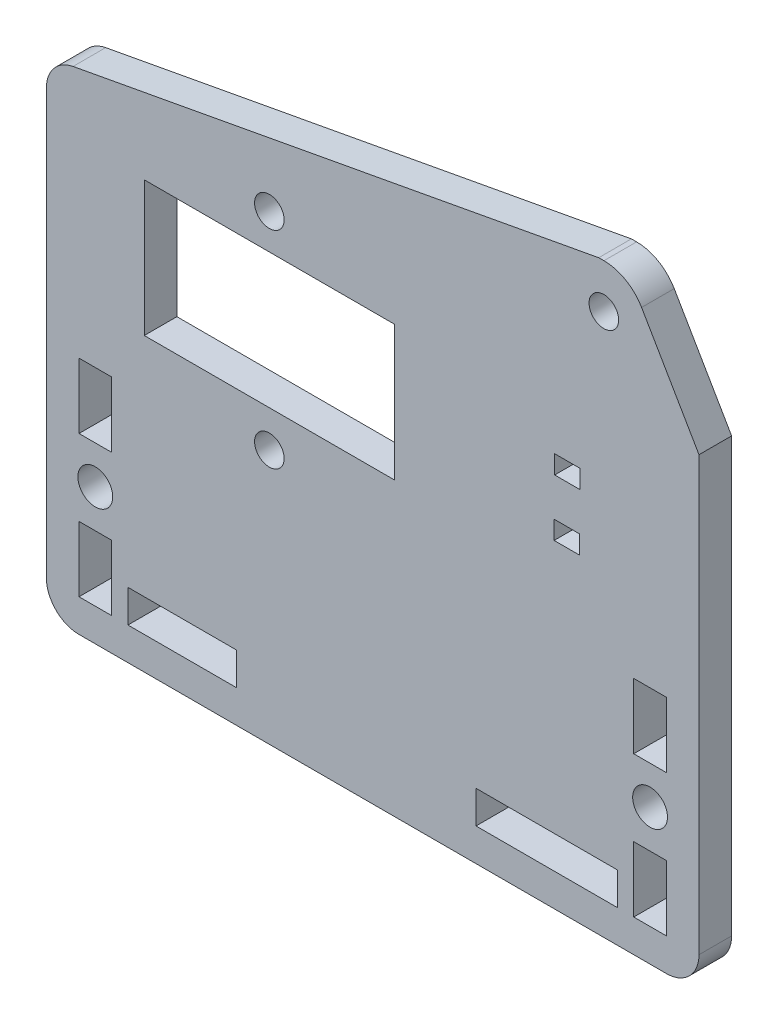
SolidWorks part; units mm, degrees
ref_plane "前视基准面" through (0, 0, 0) normal (0, 0, 1) x (1, 0, 0)
ref_plane "上视基准面" through (0, 0, 0) normal (0, 1, 0) x (1, 0, 0)
ref_plane "右视基准面" through (0, 0, 0) normal (1, 0, 0) x (0, 0, -1)
ref_plane "基准面4" through (0, 0, 0) normal (0, 0, -1) x (-1, 0, 0)
sketch "草图1" plane through (0, 0, 0) normal (0, 0, -1) x (-1, 0, 0)
  line L0 (-3.001, -11.9653) -> (-6.001, -11.9653)
  line L1 (-6.001, -11.9653) -> (-6.001, -5.9643)
  line L2 (-6.001, -5.9643) -> (-3.001, -5.9643)
  line L3 (-3.001, -5.9643) -> (-3.001, -11.9653)
  line L4 (-57, -27.9644) -> (-3, -27.9644)
  line L5 (0, -24.9644) -> (0, 14.0356)
  line L6 (-2.4546, 16.9856) -> (-50.7826, 25.9213)
  line L7 (-50.7826, 25.9213) -> (-51.2628, 25.9213)
  line L8 (-54.7215, 23.9306) -> (-60, 14.8445)
  line L9 (-60, 14.8445) -> (-60, -24.9644)
  line L10 (-3.001, -18.9633) -> (-3.001, -24.9643)
  line L11 (-3.001, -24.9643) -> (-6.001, -24.9643)
  line L12 (-6.001, -24.9643) -> (-6.001, -18.9633)
  line L13 (-6.001, -18.9633) -> (-3.001, -18.9633)
  line L14 (-54, -18.9633) -> (-54, -24.9643)
  line L15 (-54, -24.9643) -> (-57, -24.9643)
  line L16 (-57, -24.9643) -> (-57, -18.9633)
  line L17 (-57, -18.9633) -> (-54, -18.9633)
  line L18 (-54, -5.9643) -> (-54, -11.9653)
  line L19 (-54, -11.9653) -> (-57, -11.9653)
  line L20 (-57, -11.9653) -> (-57, -5.9643)
  line L21 (-57, -5.9643) -> (-54, -5.9643)
  line L22 (-7.5, -21.9643) -> (-7.5, -24.9643)
  line L23 (-7.5, -24.9643) -> (-17.5, -24.9643)
  line L24 (-17.5, -24.9643) -> (-17.5, -21.9643)
  line L25 (-17.5, -21.9643) -> (-7.5, -21.9643)
  line L26 (-39.5, -21.9643) -> (-39.5, -24.9643)
  line L27 (-39.5, -24.9643) -> (-52.499, -24.9643)
  line L28 (-52.499, -24.9643) -> (-52.499, -21.9643)
  line L29 (-52.499, -21.9643) -> (-39.5, -21.9643)
  line L30 (-46.731, 8.2907) -> (-46.731, 6.5977)
  line L31 (-46.731, 6.5977) -> (-49.06, 6.5977)
  line L32 (-49.06, 6.5977) -> (-49.06, 8.2907)
  line L33 (-49.06, 8.2907) -> (-46.731, 8.2907)
  line L34 (-46.679, 3.0517) -> (-46.679, 1.3587)
  line L35 (-46.679, 1.3587) -> (-49.008, 1.3587)
  line L36 (-49.008, 1.3587) -> (-49.008, 3.0517)
  line L37 (-49.008, 3.0517) -> (-46.679, 3.0517)
  line L38 (-9, 11.2347) -> (-9, -1.1643)
  line L39 (-9, -1.1643) -> (-32, -1.1643)
  line L40 (-32, -1.1643) -> (-32, 11.2347)
  line L41 (-32, 11.2347) -> (-9, 11.2347)
  arc A0 (-60, -24.9644) -> (-57, -27.9644) centre (-57, -24.9644) ccw
  arc A1 (-3, -27.9644) -> (0, -24.9644) centre (-3, -24.9644) ccw
  arc A2 (0, 14.0356) -> (-2.4546, 16.9856) centre (-3, 14.0356) ccw
  arc A3 (-51.2628, 25.9213) -> (-54.7215, 23.9306) centre (-51.2628, 21.9213) ccw
  circle A4 centre (-55.5, -15.4643) radius 1.359
  circle A5 centre (-4.5, -15.4643) radius 1.359
  circle A6 centre (-20.499, -4.5353) radius 1.359
  circle A7 centre (-20.499, 14.4657) radius 1.359
  circle A8 centre (-51.251, 21.8697) radius 1.359
extrude "凸台-拉伸1" add sketch "草图1" against normal blind 3
sketch "草图2" plane through (0, 0, 3) normal (0, 0, 1) x (1, 0, 0)
  circle A0 centre (55.5, -15.4643) radius 1.6
  circle A1 centre (4.5, -15.4643) radius 1.6
  dimension "D1" = 3.2
extrude "切除-拉伸1" cut sketch "草图2" against normal through all
